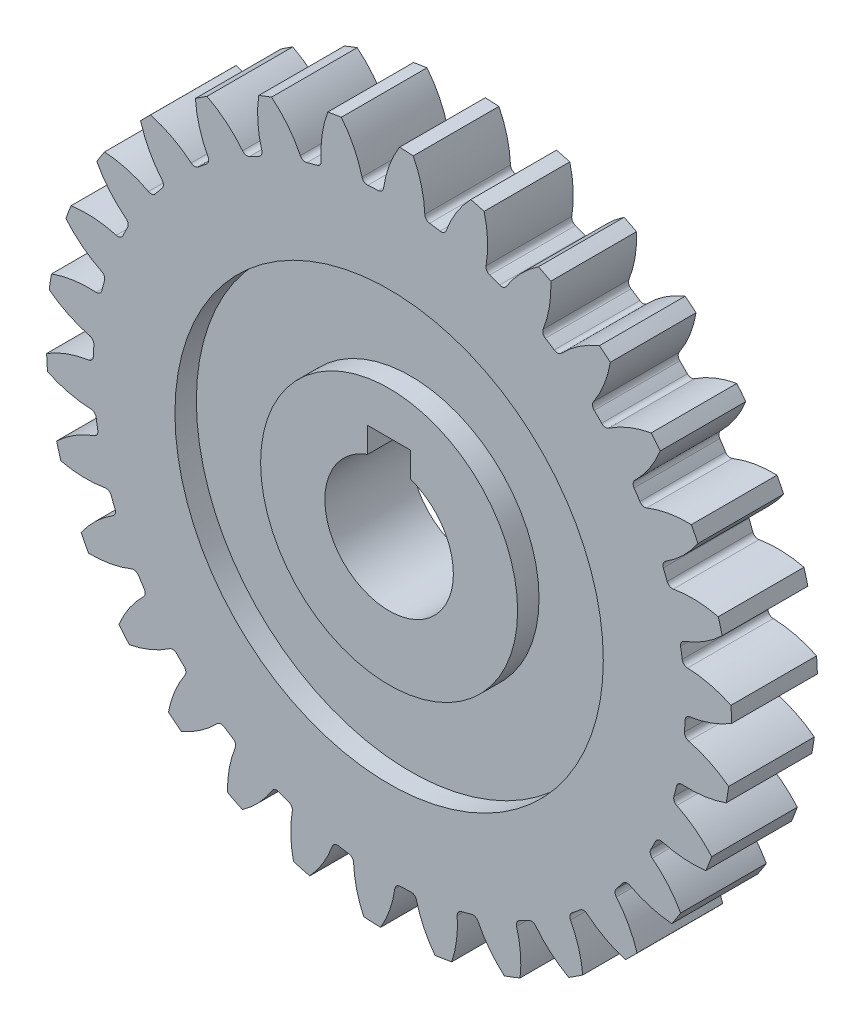
SolidWorks part; units mm, degrees
ref_plane "Alzado" through (0, 0, 0) normal (0, 0, 1) x (1, 0, 0)
ref_plane "Planta" through (0, 0, 0) normal (0, 1, 0) x (1, 0, 0)
ref_plane "Vista lateral" through (0, 0, 0) normal (1, 0, 0) x (0, 0, -1)
sketch "Croquis1" plane through (0, 0, 0) normal (0, 0, 1) x (1, 0, 0)
  circle A0 centre (0, 0) radius 80
  dimension "D1" = 160
extrude "Saliente-Extruir1" add sketch "Croquis1" along normal blind 20
sketch "Croquis2" plane through (0, 0, 20) normal (0, 0, 1) x (1, 0, 0)
  circle A0 centre (0, 0) radius 80
  arc A2 (-2.5333, 68.7033) -> (-4.9822, 68.5692) centre (0, 0) ccw
  arc A3 (2.4407, 79.9628) -> (-1.294, 69.8203) centre (24.1045, 66.2267) ccw
  arc A4 (-11.1557, 79.2184) -> (-6.336, 69.5443) centre (-31.1904, 63.1993) cw
  arc A5 (-2.5333, 68.7033) -> (-1.294, 69.8203) centre (-2.5812, 70.0024) ccw
  arc A6 (-4.9822, 68.5692) -> (-6.336, 69.5443) centre (-5.0764, 69.8658) cw
  circle M9 centre (0, 0) radius 80
  dimension "D1" = 137.5
  dimension "D2" = 1.3
  dimension "D3" = 160
extrude "Cortar-Extruir2" cut sketch "Croquis2" against normal through all contours A6 A2 A5 A3 A4 M9
pattern_circular "MatrizC1" count 30 every 12 about axis through (0.0188, -0.3442, 0) along (0, 0, 1) of "Cortar-Extruir2"
sketch "Croquis3" plane through (0, 0, 20) normal (0, 0, 1) x (1, 0, 0)
  circle A0 centre (0, 0) radius 50
  dimension "D1" = 100
extrude "Cortar-Extruir3" cut sketch "Croquis3" against normal blind 5
sketch "Croquis4" plane through (0, 0, 15) normal (0, 0, 1) x (1, 0, 0)
  circle A0 centre (0, 0) radius 15
  dimension "D1" = 30
extrude "Cortar-Extruir4" cut sketch "Croquis4" against normal through all
sketch "Croquis6" plane through (0, 0, 15) normal (0, 0, 1) x (1, 0, 0)
  circle A0 centre (0, 0) radius 15
  circle A1 centre (0, 0) radius 30
  dimension "D1" = 30
  dimension "D2" = 60
extrude "Saliente-Extruir2" add sketch "Croquis6" along normal blind 5
sketch "Croquis7" plane through (0, 0, 20) normal (0, 0, 1) x (1, 0, 0)
  line L1 (-5, 10) -> (5, 10)
  line L2 (-5, 10) -> (-5, 20)
  line L3 (-5, 20) -> (5, 20)
  line L4 (5, 10) -> (5, 20)
  line L5 (-5, 10) -> (5, 20) construction
  line L6 (-5, 20) -> (5, 10) construction
  circle A0 centre (0, 0) radius 15 construction
  point P0 (0, 15)
  dimension "D1" = 10
  dimension "D2" = 10
extrude "Cortar-Extruir5" cut sketch "Croquis7" against normal through all
